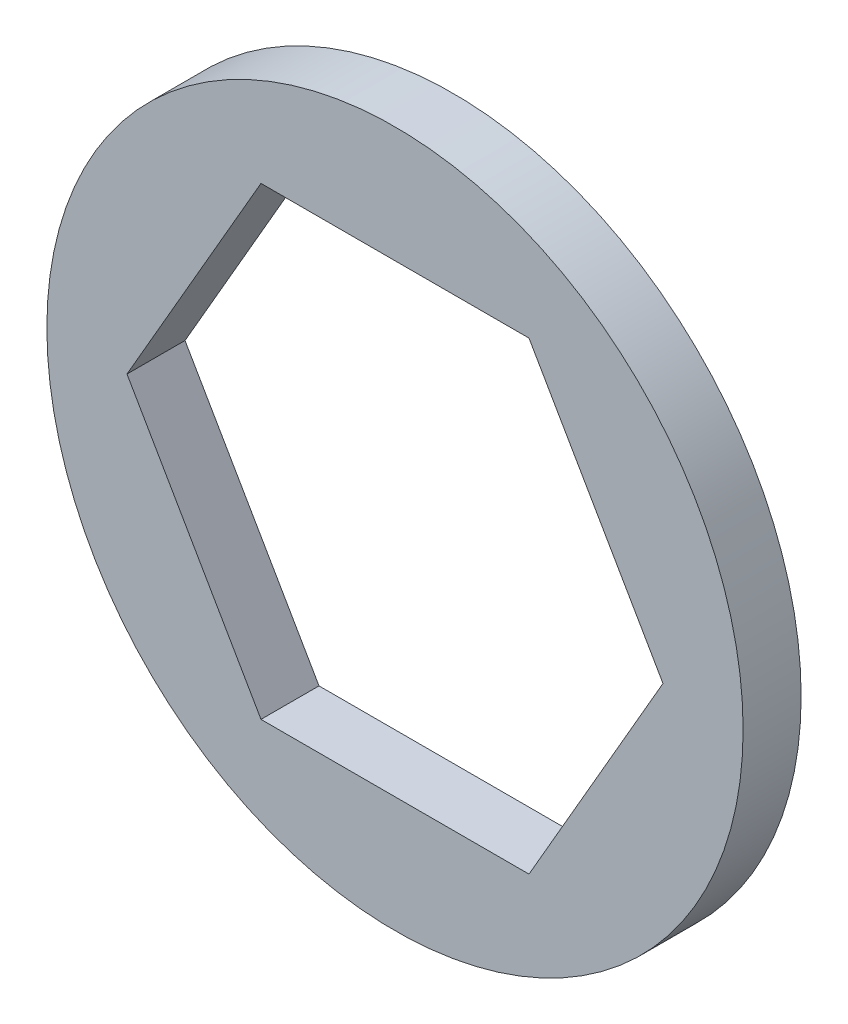
SolidWorks part; units mm, degrees
material "PET"
ref_plane "Front Plane" through (0, 0, 0) normal (0, 0, 1) x (1, 0, 0)
ref_plane "Top Plane" through (0, 0, 0) normal (0, 1, 0) x (1, 0, 0)
ref_plane "Right Plane" through (0, 0, 0) normal (1, 0, 0) x (0, 0, -1)
sketch "Sketch1" plane through (0, 0, 0) normal (0, 0, 1) x (1, 0, 0)
  line L1 (7.3323, 0) -> (3.6662, 6.35)
  line L2 (3.6662, 6.35) -> (-3.6662, 6.35)
  line L3 (-3.6662, 6.35) -> (-7.3323, 0)
  line L4 (-7.3323, 0) -> (-3.6662, -6.35)
  line L5 (-3.6662, -6.35) -> (3.6662, -6.35)
  line L6 (3.6662, -6.35) -> (7.3323, 0)
  circle A0 centre (0, 0) radius 9.525
  circle A1 centre (0, 0) radius 6.35 construction
  dimension "D1" = 12.7
  dimension "D2" = 19.05
extrude "Boss-Extrude1" add sketch "Sketch1" along normal blind 1.5875
